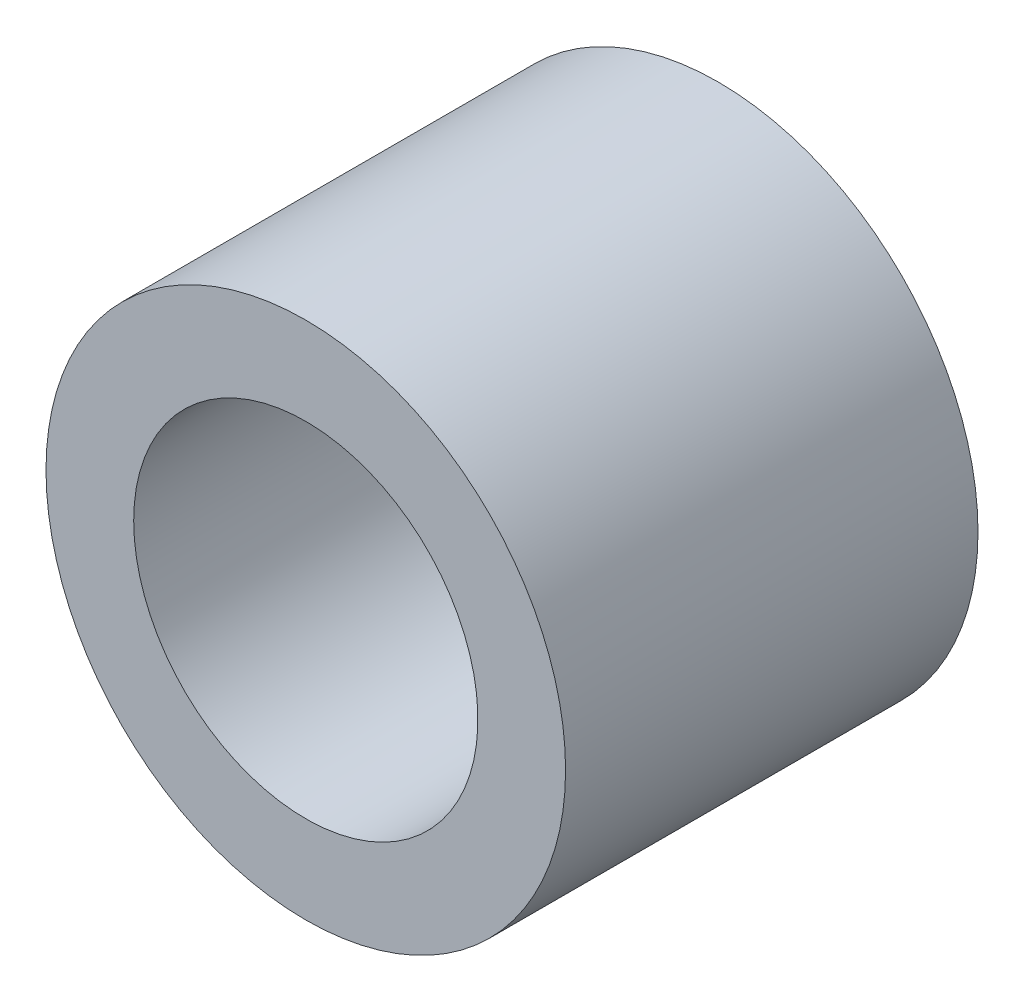
SolidWorks part; units mm, degrees
ref_plane "Front Plane" through (0, 0, 0) normal (0, 0, 1) x (1, 0, 0)
ref_plane "Top Plane" through (0, 0, 0) normal (0, 1, 0) x (1, 0, 0)
ref_plane "Right Plane" through (0, 0, 0) normal (1, 0, 0) x (0, 0, -1)
ref_plane "Plane1" through (0, 0, 0) normal (0, -1, 0) x (1, 0, 0)
sketch "Sketch1" plane through (0, 0, 0) normal (0, -1, 0) x (1, 0, 0)
  line L0 (4, 3.175) -> (2.65, 3.175)
  line L1 (2.65, 3.175) -> (2.65, -3.175)
  line L2 (2.65, -3.175) -> (4, -3.175)
  line L3 (4, -3.175) -> (4, 3.175)
  line L4 (0, 3.175) -> (0, -3.175) construction
revolve "Revolve1" add sketch "Sketch1" angle 360 about L4
